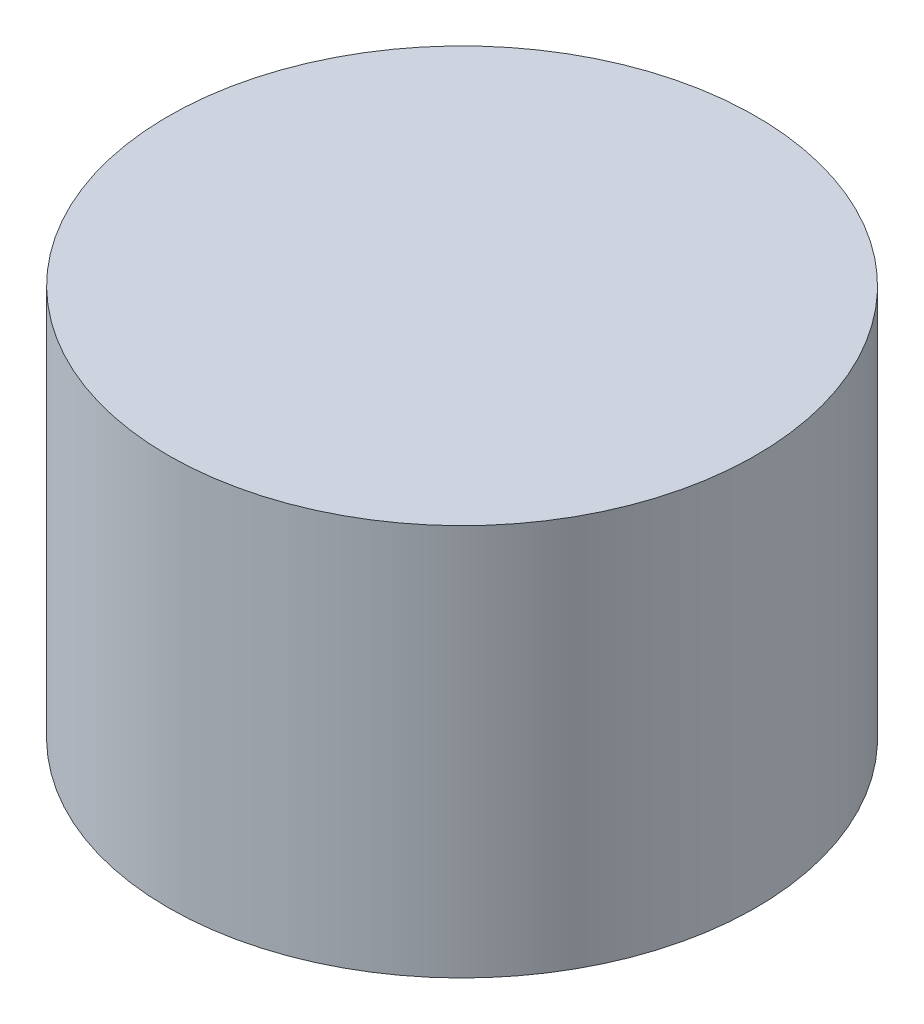
SolidWorks part; units mm, degrees
ref_plane "Front Plane" through (0, 0, 0) normal (0, 0, 1) x (1, 0, 0)
ref_plane "Top Plane" through (0, 0, 0) normal (0, 1, 0) x (1, 0, 0)
ref_plane "Right Plane" through (0, 0, 0) normal (1, 0, 0) x (0, 0, -1)
sketch "Sketch1" plane through (0, 0, 0) normal (0, 1, 0) x (1, 0, 0)
  circle A0 centre (0, 0) radius 1.5
  dimension "D1" = 3
extrude "Boss-Extrude1" add sketch "Sketch1" along normal mid plane 2
